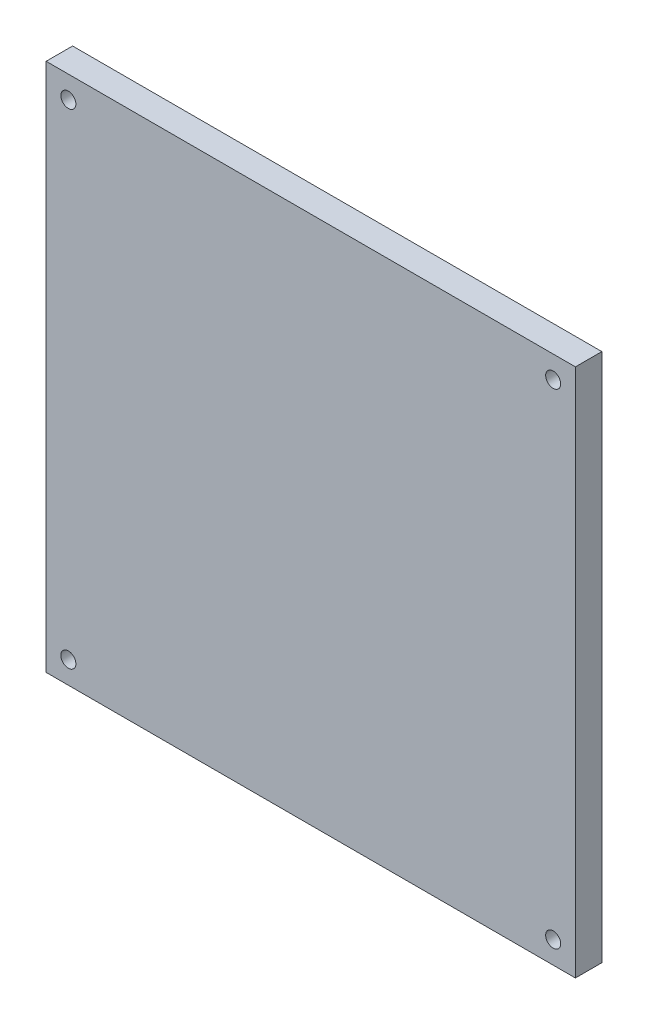
SolidWorks part; units mm, degrees
material "ABS"
ref_plane "Plan de face" through (0, 0, 0) normal (0, 0, 1) x (1, 0, 0)
ref_plane "Plan de dessus" through (0, 0, 0) normal (0, 1, 0) x (1, 0, 0)
ref_plane "Plan de droite" through (0, 0, 0) normal (1, 0, 0) x (0, 0, -1)
sketch "Esquisse2" plane through (0, 0, 0) normal (0, 0, 1) x (1, 0, 0)
  line L1 (-50, 50) -> (50, 50)
  line L2 (-50, 50) -> (-50, -50)
  line L3 (-50, -50) -> (50, -50)
  line L4 (50, 50) -> (50, -50)
  line L5 (-50, 50) -> (50, -50) construction
  line L6 (-50, -50) -> (50, 50) construction
  point P0 (0, 0)
  dimension "D1" = 100
  dimension "D2" = 100
extrude "Boss.-Extru.1" add sketch "Esquisse2" along normal blind 5
sketch "Esquisse3" plane through (0, 0, 5) normal (0, 0, 1) x (1, 0, 0)
  line L0 (-50, 50) -> (-50, -50) construction
  line L1 (50, 50) -> (-50, 50) construction
  line L2 (-50, -50) -> (50, -50) construction
  line L3 (50, -50) -> (50, 50) construction
  line L5 (-50, -50) -> (50, -50) construction
  circle A0 centre (-45.8, 45.8) radius 1.42
  circle A1 centre (-45.8, -45.8) radius 1.42
  circle A2 centre (45.8, -45.8) radius 1.42
  circle A3 centre (45.8, 45.8) radius 1.42
  dimension "D9" = 2.84
  dimension "D10" = 2.84
  dimension "D11" = 2.84
  dimension "D12" = 2.84
  dimension "D3" = 4.2
  dimension "D2" = 4.2
  dimension "D4" = 4.2
  dimension "D5" = 4.2
  dimension "D6" = 4.2
  dimension "D7" = 4.2
  dimension "D8" = 4.2
  dimension "D13" = 4.2
extrude "Enlèv. mat.-Extru.1" cut sketch "Esquisse3" against normal blind 5
